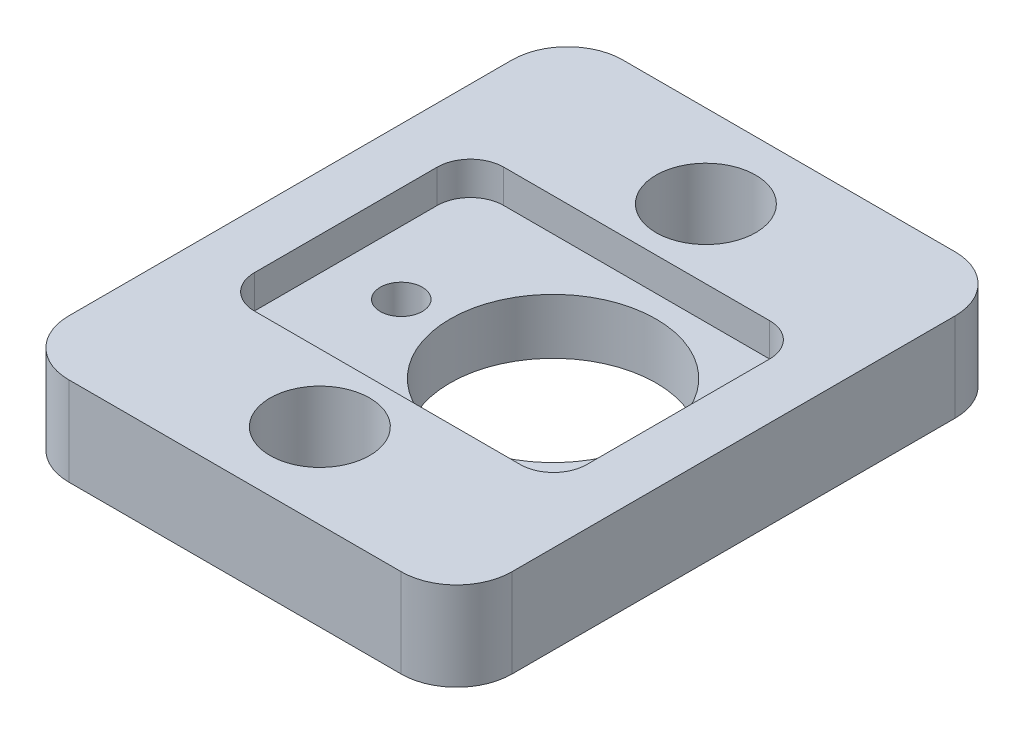
SolidWorks part; units mm, degrees
ref_plane "Front Plane" through (0, 0, 0) normal (0, 0, 1) x (1, 0, 0)
ref_plane "Top Plane" through (0, 0, 0) normal (0, 1, 0) x (1, 0, 0)
ref_plane "Right Plane" through (0, 0, 0) normal (1, 0, 0) x (0, 0, -1)
sketch "Sketch1" plane through (0, 0, 0) normal (0, 1, 0) x (1, 0, 0)
  line L1 (2, 0) -> (14, 0)
  line L2 (0, -2) -> (0, -18)
  line L3 (2, -20) -> (14, -20)
  line L4 (16, -2) -> (16, -18)
  arc A0 (0, -18) -> (2, -20) centre (2, -18) ccw
  arc A1 (14, -20) -> (16, -18) centre (14, -18) ccw
  arc A2 (14, 0) -> (16, -2) centre (14, -2) cw
  arc A3 (2, 0) -> (0, -2) centre (2, -2) ccw
  point P7 (0, -20)
  point P12 (16, 0)
  point P15 (0, 0)
  dimension "D3" = 2
  dimension "D1" = 16
  dimension "D2" = 20
extrude "Boss-Extrude1" add sketch "Sketch1" along normal blind 3.2
sketch "Sketch2" plane through (0, 3.2, 0) normal (0, 1, 0) x (1, 0, 0)
  line L0 (14, 0) -> (2, 0) construction
  line L1 (3.2, -5.5) -> (12.8, -5.5)
  line L2 (2, -6.7) -> (2, -13.3)
  line L3 (3.2, -14.5) -> (12.8, -14.5)
  line L4 (14, -6.7) -> (14, -13.3)
  line L5 (16, -18) -> (16, -2) construction
  arc A0 (2, -13.3) -> (3.2, -14.5) centre (3.2, -13.3) ccw
  arc A1 (12.8, -14.5) -> (14, -13.3) centre (12.8, -13.3) ccw
  arc A2 (12.8, -5.5) -> (14, -6.7) centre (12.8, -6.7) cw
  arc A3 (3.2, -5.5) -> (2, -6.7) centre (3.2, -6.7) ccw
  point P4 (8, -5.5)
  point P9 (2, -14.5)
  point P14 (14, -5.5)
  point P17 (2, -5.5)
  dimension "D4" = 1.2
  dimension "D1" = 12
  dimension "D2" = 9
  dimension "D3" = 5.5
  dimension "D5" = 2
extrude "Cut-Extrude1" cut sketch "Sketch2" against normal blind 1.2
sketch "Sketch3" plane through (0, 2, 0) normal (0, 1, 0) x (1, 0, 0)
  line L0 (14, -13.3) -> (14, -6.7) construction
  circle A0 centre (9.5, -10.0174) radius 3.72
  dimension "D1" = 7.44
  dimension "D2" = 4.5
extrude "Cut-Extrude2" cut sketch "Sketch3" against normal through all
sketch "Sketch4" plane through (0, 3.2, 0) normal (0, 1, 0) x (1, 0, 0)
  line L1 (0, -2) -> (0, -18) construction
  line L2 (14, 0) -> (2, 0) construction
  circle A0 centre (8, -3) radius 1.8
  circle A2 centre (8, -16.9366) radius 1.8
  dimension "D1" = 3
  dimension "D2" = 8
extrude "Cut-Extrude3" cut sketch "Sketch4" against normal through all
sketch "Sketch5" plane through (0, 2, 0) normal (0, 1, 0) x (1, 0, 0)
  circle A0 centre (4.2868, -10.2839) radius 0.76
  circle A1 centre (9.5, -10.0174) radius 3.72 construction
  dimension "D1" = 1.5
  dimension "D2" = 1.52
extrude "Cut-Extrude4" cut sketch "Sketch5" against normal blind 10
